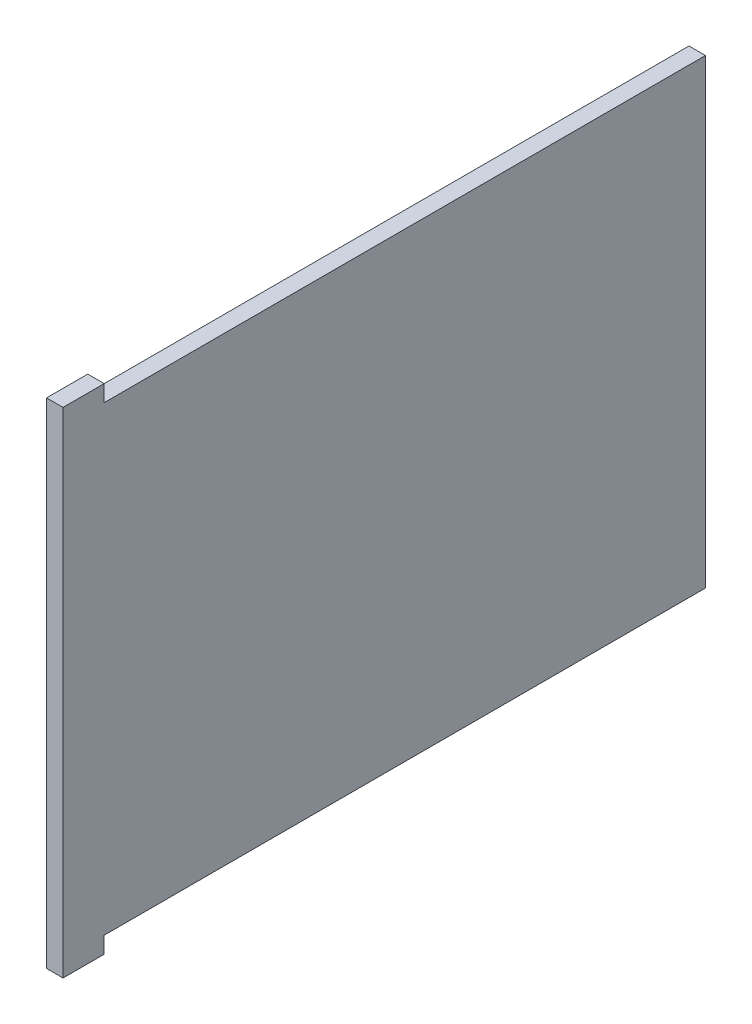
SolidWorks part; units mm, degrees
ref_plane "前视基准面" through (0, 0, 0) normal (0, 0, 1) x (1, 0, 0)
ref_plane "上视基准面" through (0, 0, 0) normal (0, 1, 0) x (1, 0, 0)
ref_plane "右视基准面" through (0, 0, 0) normal (1, 0, 0) x (0, 0, -1)
other "Configuration Table"
sketch "草图1" plane through (0, 0, 0) normal (1, 0, 0) x (0, 0, -1)
  line L1 (0, 0) -> (78, 0)
  line L2 (0, 0) -> (0, 60)
  line L3 (0, 60) -> (78, 60)
  line L4 (78, 0) -> (78, 60)
  line L5 (5, 60) -> (78, 60)
  line L6 (5, 60) -> (5, 58)
  line L7 (5, 58) -> (78, 58)
  line L8 (78, 60) -> (78, 58)
  line L9 (78, 0) -> (5, 0)
  line L10 (78, 0) -> (78, 2)
  line L11 (78, 2) -> (5, 2)
  line L12 (5, 0) -> (5, 2)
extrude "凸台-拉伸1" add sketch "草图1" along normal blind 2 contours L1 L12 L11 L4 L7 L6 L3 L2
